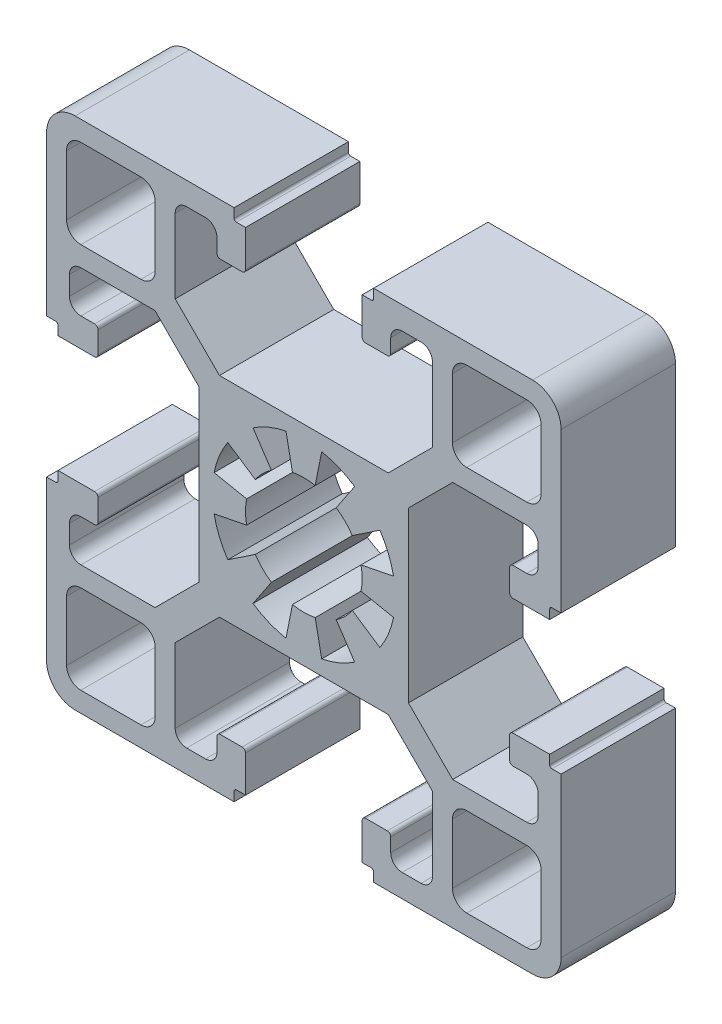
SolidWorks part; units mm, degrees
ref_plane "前视基准面" through (0, 0, 0) normal (0, 0, 1) x (1, 0, 0)
ref_plane "上视基准面" through (0, 0, 0) normal (0, 1, 0) x (1, 0, 0)
ref_plane "右视基准面" through (0, 0, 0) normal (1, 0, 0) x (0, 0, -1)
sketch "草图1" plane through (0, 0, 0) normal (0, 0, 1) x (1, 0, 0)
  line L0 (-29.0757, 38.982) -> (-42.9757, 38.982)
  line L1 (-45.4757, 36.482) -> (-45.4757, 22.582)
  line L2 (-28.0757, 37.982) -> (-28.0757, 34.782)
  line L3 (-28.3757, 34.482) -> (-30.2757, 34.482)
  line L4 (-30.5757, 34.782) -> (-30.5757, 35.982)
  line L5 (-31.5757, 36.982) -> (-33.2257, 36.982)
  line L6 (-34.2257, 35.982) -> (-34.2257, 29.4998)
  line L7 (-42.4757, 29.482) -> (-37.2257, 29.482)
  line L8 (-35.9757, 30.732) -> (-35.9757, 35.982)
  line L9 (-37.2257, 37.232) -> (-42.4757, 37.232)
  line L10 (-43.7257, 35.982) -> (-43.7257, 30.732)
  line L11 (-35.9935, 27.732) -> (-42.4757, 27.732)
  line L12 (-43.4757, 26.732) -> (-43.4757, 25.082)
  line L13 (-42.4757, 24.082) -> (-41.2757, 24.082)
  line L14 (-40.9757, 23.782) -> (-40.9757, 21.882)
  line L15 (-41.2757, 21.582) -> (-44.4757, 21.582)
  line L16 (-28.0757, 37.982) -> (-28.8757, 37.982)
  line L17 (-29.0757, 38.182) -> (-29.0757, 38.982)
  line L18 (-45.4757, 22.582) -> (-44.6757, 22.582)
  line L19 (-44.4757, 22.382) -> (-44.4757, 21.582)
  line L20 (-32.1257, 23.8643) -> (-32.1257, 9.0998)
  line L21 (-30.358, 7.332) -> (-15.5935, 7.332)
  line L22 (-13.8257, 9.0998) -> (-13.8257, 23.8643)
  line L23 (-15.5935, 25.632) -> (-30.358, 25.632)
  line L24 (-34.2257, 29.4998) -> (-30.358, 25.632)
  line L25 (-35.9935, 27.732) -> (-32.1257, 23.8643)
  line L26 (-16.8757, 38.982) -> (-2.9757, 38.982)
  line L27 (-0.4757, 36.482) -> (-0.4757, 22.582)
  line L28 (-17.8757, 37.982) -> (-17.8757, 34.782)
  line L29 (-17.5757, 34.482) -> (-15.6757, 34.482)
  line L30 (-15.3757, 34.782) -> (-15.3757, 35.982)
  line L31 (-14.3757, 36.982) -> (-12.7257, 36.982)
  line L32 (-11.7257, 35.982) -> (-11.7257, 29.4998)
  line L33 (-3.4757, 29.482) -> (-8.7257, 29.482)
  line L34 (-9.9757, 30.732) -> (-9.9757, 35.982)
  line L35 (-8.7257, 37.232) -> (-3.4757, 37.232)
  line L36 (-2.2257, 35.982) -> (-2.2257, 30.732)
  line L37 (-9.958, 27.732) -> (-3.4757, 27.732)
  line L38 (-2.4757, 26.732) -> (-2.4757, 25.082)
  line L39 (-3.4757, 24.082) -> (-4.6757, 24.082)
  line L40 (-4.9757, 23.782) -> (-4.9757, 21.882)
  line L41 (-4.6757, 21.582) -> (-1.4757, 21.582)
  line L42 (-17.8757, 37.982) -> (-17.0757, 37.982)
  line L43 (-16.8757, 38.182) -> (-16.8757, 38.982)
  line L44 (-0.4757, 22.582) -> (-1.2757, 22.582)
  line L45 (-1.4757, 22.382) -> (-1.4757, 21.582)
  line L46 (-11.7257, 29.4998) -> (-15.5935, 25.632)
  line L47 (-9.958, 27.732) -> (-13.8257, 23.8643)
  line L48 (-29.0757, -6.018) -> (-42.9757, -6.018)
  line L49 (-45.4757, -3.518) -> (-45.4757, 10.382)
  line L50 (-28.0757, -5.018) -> (-28.0757, -1.818)
  line L51 (-28.3757, -1.518) -> (-30.2757, -1.518)
  line L52 (-30.5757, -1.818) -> (-30.5757, -3.018)
  line L53 (-31.5757, -4.018) -> (-33.2257, -4.018)
  line L54 (-34.2257, -3.018) -> (-34.2257, 3.4643)
  line L55 (-42.4757, 3.482) -> (-37.2257, 3.482)
  line L56 (-35.9757, 2.232) -> (-35.9757, -3.018)
  line L57 (-37.2257, -4.268) -> (-42.4757, -4.268)
  line L58 (-43.7257, -3.018) -> (-43.7257, 2.232)
  line L59 (-35.9935, 5.232) -> (-42.4757, 5.232)
  line L60 (-43.4757, 6.232) -> (-43.4757, 7.882)
  line L61 (-42.4757, 8.882) -> (-41.2757, 8.882)
  line L62 (-40.9757, 9.182) -> (-40.9757, 11.082)
  line L63 (-41.2757, 11.382) -> (-44.4757, 11.382)
  line L64 (-28.0757, -5.018) -> (-28.8757, -5.018)
  line L65 (-29.0757, -5.218) -> (-29.0757, -6.018)
  line L66 (-45.4757, 10.382) -> (-44.6757, 10.382)
  line L67 (-44.4757, 10.582) -> (-44.4757, 11.382)
  line L68 (-34.2257, 3.4643) -> (-30.358, 7.332)
  line L69 (-35.9935, 5.232) -> (-32.1257, 9.0998)
  line L70 (-16.8757, -6.018) -> (-2.9757, -6.018)
  line L71 (-0.4757, -3.518) -> (-0.4757, 10.382)
  line L72 (-17.8757, -5.018) -> (-17.8757, -1.818)
  line L73 (-17.5757, -1.518) -> (-15.6757, -1.518)
  line L74 (-15.3757, -1.818) -> (-15.3757, -3.018)
  line L75 (-14.3757, -4.018) -> (-12.7257, -4.018)
  line L76 (-11.7257, -3.018) -> (-11.7257, 3.4643)
  line L77 (-3.4757, 3.482) -> (-8.7257, 3.482)
  line L78 (-9.9757, 2.232) -> (-9.9757, -3.018)
  line L79 (-8.7257, -4.268) -> (-3.4757, -4.268)
  line L80 (-2.2257, -3.018) -> (-2.2257, 2.232)
  line L81 (-9.958, 5.232) -> (-3.4757, 5.232)
  line L82 (-2.4757, 6.232) -> (-2.4757, 7.882)
  line L83 (-3.4757, 8.882) -> (-4.6757, 8.882)
  line L84 (-4.9757, 9.182) -> (-4.9757, 11.082)
  line L85 (-4.6757, 11.382) -> (-1.4757, 11.382)
  line L86 (-17.8757, -5.018) -> (-17.0757, -5.018)
  line L87 (-16.8757, -5.218) -> (-16.8757, -6.018)
  line L88 (-0.4757, 10.382) -> (-1.2757, 10.382)
  line L89 (-1.4757, 10.582) -> (-1.4757, 11.382)
  line L90 (-11.7257, 3.4643) -> (-15.5935, 7.332)
  line L91 (-9.958, 5.232) -> (-13.8257, 9.0998)
  line L92 (-27.4203, 9.8303) -> (-25.8092, 12.2416)
  line L93 (-24.5365, 8.6358) -> (-23.9707, 11.48)
  line L94 (-21.415, 8.6358) -> (-21.9808, 11.48)
  line L95 (-18.5312, 9.8303) -> (-20.1423, 12.2416)
  line L96 (-16.324, 12.0375) -> (-18.7352, 13.6486)
  line L97 (-15.1295, 14.9213) -> (-17.9737, 15.4871)
  line L98 (-15.1295, 18.0428) -> (-17.9737, 17.477)
  line L99 (-16.324, 20.9266) -> (-18.7352, 19.3155)
  line L100 (-18.5312, 23.1338) -> (-20.1423, 20.7225)
  line L101 (-21.415, 24.3283) -> (-21.9808, 21.4841)
  line L102 (-24.5365, 24.3283) -> (-23.9707, 21.4841)
  line L103 (-27.4203, 23.1338) -> (-25.8092, 20.7225)
  line L104 (-29.6275, 20.9266) -> (-27.2162, 19.3155)
  line L105 (-30.822, 18.0428) -> (-27.9777, 17.477)
  line L106 (-30.822, 14.9213) -> (-27.9777, 15.4871)
  line L107 (-29.6275, 12.0375) -> (-27.2162, 13.6486)
  arc A0 (-42.9757, 38.982) -> (-45.4757, 36.482) centre (-42.9757, 36.482) ccw
  arc A1 (-28.3757, 34.482) -> (-28.0757, 34.782) centre (-28.3757, 34.782) ccw
  arc A2 (-30.5757, 34.782) -> (-30.2757, 34.482) centre (-30.2757, 34.782) ccw
  arc A3 (-30.5757, 35.982) -> (-31.5757, 36.982) centre (-31.5757, 35.982) ccw
  arc A4 (-33.2257, 36.982) -> (-34.2257, 35.982) centre (-33.2257, 35.982) ccw
  arc A5 (-37.2257, 29.482) -> (-35.9757, 30.732) centre (-37.2257, 30.732) ccw
  arc A6 (-35.9757, 35.982) -> (-37.2257, 37.232) centre (-37.2257, 35.982) ccw
  arc A7 (-42.4757, 37.232) -> (-43.7257, 35.982) centre (-42.4757, 35.982) ccw
  arc A8 (-43.7257, 30.732) -> (-42.4757, 29.482) centre (-42.4757, 30.732) ccw
  arc A9 (-42.4757, 27.732) -> (-43.4757, 26.732) centre (-42.4757, 26.732) ccw
  arc A10 (-43.4757, 25.082) -> (-42.4757, 24.082) centre (-42.4757, 25.082) ccw
  arc A11 (-40.9757, 23.782) -> (-41.2757, 24.082) centre (-41.2757, 23.782) ccw
  arc A12 (-41.2757, 21.582) -> (-40.9757, 21.882) centre (-41.2757, 21.882) ccw
  arc A13 (-29.0757, 38.182) -> (-28.8757, 37.982) centre (-28.8757, 38.182) ccw
  arc A14 (-44.4757, 22.382) -> (-44.6757, 22.582) centre (-44.6757, 22.382) ccw
  arc A15 (-23.9707, 11.48) -> (-21.9808, 11.48) centre (-22.9757, 16.482) ccw
  arc A16 (-20.1423, 12.2416) -> (-18.7352, 13.6486) centre (-22.9757, 16.482) ccw
  arc A17 (-17.9737, 15.4871) -> (-17.9737, 17.477) centre (-22.9757, 16.482) ccw
  arc A18 (-18.7352, 19.3155) -> (-20.1423, 20.7225) centre (-22.9757, 16.482) ccw
  arc A19 (-21.9808, 21.4841) -> (-23.9707, 21.4841) centre (-22.9757, 16.482) ccw
  arc A20 (-25.8092, 20.7225) -> (-27.2162, 19.3155) centre (-22.9757, 16.482) ccw
  arc A21 (-27.9777, 17.477) -> (-27.9777, 15.4871) centre (-22.9757, 16.482) ccw
  arc A22 (-27.2162, 13.6486) -> (-25.8092, 12.2416) centre (-22.9757, 16.482) ccw
  arc A23 (-27.4203, 9.8303) -> (-24.5365, 8.6358) centre (-22.9757, 16.482) ccw
  arc A24 (-21.415, 8.6358) -> (-18.5312, 9.8303) centre (-22.9757, 16.482) ccw
  arc A25 (-16.324, 12.0375) -> (-15.1295, 14.9213) centre (-22.9757, 16.482) ccw
  arc A26 (-15.1295, 18.0428) -> (-16.324, 20.9266) centre (-22.9757, 16.482) ccw
  arc A27 (-18.5312, 23.1338) -> (-21.415, 24.3283) centre (-22.9757, 16.482) ccw
  arc A28 (-24.5365, 24.3283) -> (-27.4203, 23.1338) centre (-22.9757, 16.482) ccw
  arc A29 (-29.6275, 20.9266) -> (-30.822, 18.0428) centre (-22.9757, 16.482) ccw
  arc A30 (-30.822, 14.9213) -> (-29.6275, 12.0375) centre (-22.9757, 16.482) ccw
  arc A31 (-0.4757, 36.482) -> (-2.9757, 38.982) centre (-2.9757, 36.482) ccw
  arc A32 (-17.8757, 34.782) -> (-17.5757, 34.482) centre (-17.5757, 34.782) ccw
  arc A33 (-15.6757, 34.482) -> (-15.3757, 34.782) centre (-15.6757, 34.782) ccw
  arc A34 (-14.3757, 36.982) -> (-15.3757, 35.982) centre (-14.3757, 35.982) ccw
  arc A35 (-11.7257, 35.982) -> (-12.7257, 36.982) centre (-12.7257, 35.982) ccw
  arc A36 (-9.9757, 30.732) -> (-8.7257, 29.482) centre (-8.7257, 30.732) ccw
  arc A37 (-8.7257, 37.232) -> (-9.9757, 35.982) centre (-8.7257, 35.982) ccw
  arc A38 (-2.2257, 35.982) -> (-3.4757, 37.232) centre (-3.4757, 35.982) ccw
  arc A39 (-3.4757, 29.482) -> (-2.2257, 30.732) centre (-3.4757, 30.732) ccw
  arc A40 (-2.4757, 26.732) -> (-3.4757, 27.732) centre (-3.4757, 26.732) ccw
  arc A41 (-3.4757, 24.082) -> (-2.4757, 25.082) centre (-3.4757, 25.082) ccw
  arc A42 (-4.6757, 24.082) -> (-4.9757, 23.782) centre (-4.6757, 23.782) ccw
  arc A43 (-4.9757, 21.882) -> (-4.6757, 21.582) centre (-4.6757, 21.882) ccw
  arc A44 (-17.0757, 37.982) -> (-16.8757, 38.182) centre (-17.0757, 38.182) ccw
  arc A45 (-1.2757, 22.582) -> (-1.4757, 22.382) centre (-1.2757, 22.382) ccw
  arc A46 (-45.4757, -3.518) -> (-42.9757, -6.018) centre (-42.9757, -3.518) ccw
  arc A47 (-28.0757, -1.818) -> (-28.3757, -1.518) centre (-28.3757, -1.818) ccw
  arc A48 (-30.2757, -1.518) -> (-30.5757, -1.818) centre (-30.2757, -1.818) ccw
  arc A49 (-31.5757, -4.018) -> (-30.5757, -3.018) centre (-31.5757, -3.018) ccw
  arc A50 (-34.2257, -3.018) -> (-33.2257, -4.018) centre (-33.2257, -3.018) ccw
  arc A51 (-35.9757, 2.232) -> (-37.2257, 3.482) centre (-37.2257, 2.232) ccw
  arc A52 (-37.2257, -4.268) -> (-35.9757, -3.018) centre (-37.2257, -3.018) ccw
  arc A53 (-43.7257, -3.018) -> (-42.4757, -4.268) centre (-42.4757, -3.018) ccw
  arc A54 (-42.4757, 3.482) -> (-43.7257, 2.232) centre (-42.4757, 2.232) ccw
  arc A55 (-43.4757, 6.232) -> (-42.4757, 5.232) centre (-42.4757, 6.232) ccw
  arc A56 (-42.4757, 8.882) -> (-43.4757, 7.882) centre (-42.4757, 7.882) ccw
  arc A57 (-41.2757, 8.882) -> (-40.9757, 9.182) centre (-41.2757, 9.182) ccw
  arc A58 (-40.9757, 11.082) -> (-41.2757, 11.382) centre (-41.2757, 11.082) ccw
  arc A59 (-28.8757, -5.018) -> (-29.0757, -5.218) centre (-28.8757, -5.218) ccw
  arc A60 (-44.6757, 10.382) -> (-44.4757, 10.582) centre (-44.6757, 10.582) ccw
  arc A61 (-2.9757, -6.018) -> (-0.4757, -3.518) centre (-2.9757, -3.518) ccw
  arc A62 (-17.5757, -1.518) -> (-17.8757, -1.818) centre (-17.5757, -1.818) ccw
  arc A63 (-15.3757, -1.818) -> (-15.6757, -1.518) centre (-15.6757, -1.818) ccw
  arc A64 (-15.3757, -3.018) -> (-14.3757, -4.018) centre (-14.3757, -3.018) ccw
  arc A65 (-12.7257, -4.018) -> (-11.7257, -3.018) centre (-12.7257, -3.018) ccw
  arc A66 (-8.7257, 3.482) -> (-9.9757, 2.232) centre (-8.7257, 2.232) ccw
  arc A67 (-9.9757, -3.018) -> (-8.7257, -4.268) centre (-8.7257, -3.018) ccw
  arc A68 (-3.4757, -4.268) -> (-2.2257, -3.018) centre (-3.4757, -3.018) ccw
  arc A69 (-2.2257, 2.232) -> (-3.4757, 3.482) centre (-3.4757, 2.232) ccw
  arc A70 (-3.4757, 5.232) -> (-2.4757, 6.232) centre (-3.4757, 6.232) ccw
  arc A71 (-2.4757, 7.882) -> (-3.4757, 8.882) centre (-3.4757, 7.882) ccw
  arc A72 (-4.9757, 9.182) -> (-4.6757, 8.882) centre (-4.6757, 9.182) ccw
  arc A73 (-4.6757, 11.382) -> (-4.9757, 11.082) centre (-4.6757, 11.082) ccw
  arc A74 (-16.8757, -5.218) -> (-17.0757, -5.018) centre (-17.0757, -5.218) ccw
  arc A75 (-1.4757, 10.582) -> (-1.2757, 10.382) centre (-1.2757, 10.582) ccw
extrude "凸台-拉伸1" add sketch "草图1" along normal blind 10
